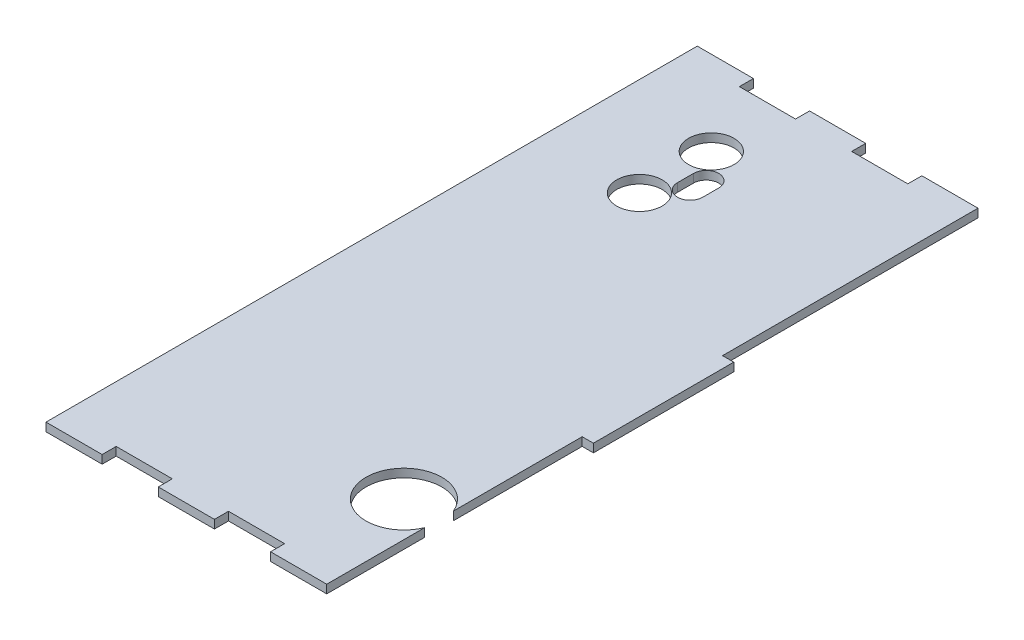
SolidWorks part; units mm, degrees
ref_plane "Front Plane" through (0, 0, 0) normal (0, 0, 1) x (1, 0, 0)
ref_plane "Top Plane" through (0, 0, 0) normal (0, 1, 0) x (1, 0, 0)
ref_plane "Right Plane" through (0, 0, 0) normal (1, 0, 0) x (0, 0, -1)
sketch "Sketch1" plane through (0, 0, 0) normal (0, 1, 0) x (1, 0, 0)
  line L0 (-50, -111) -> (-50, -116)
  line L1 (30, 111) -> (10, 111)
  line L2 (50, 111) -> (50, 25)
  line L3 (30, -111) -> (10, -111)
  line L4 (-50, 111) -> (-50, -111)
  line L5 (50, 111) -> (-50, -111) construction
  line L6 (50, -111) -> (-50, 111) construction
  line L7 (-50, -116) -> (-30, -116)
  line L8 (-30, -116) -> (-30, -111)
  line L9 (-10, -111) -> (-10, -116)
  line L10 (-10, -116) -> (10, -116)
  line L11 (10, -116) -> (10, -111)
  line L12 (30, -111) -> (30, -116)
  line L13 (30, -116) -> (50, -116)
  line L14 (50, -116) -> (50, -111)
  line L15 (-50, 0) -> (50, 0) construction
  line L16 (0, -116) -> (0, 116) construction
  line L17 (50, 116) -> (50, 111)
  line L18 (30, 116) -> (50, 116)
  line L19 (30, 111) -> (30, 116)
  line L20 (10, 116) -> (10, 111)
  line L21 (-10, 116) -> (10, 116)
  line L22 (-10, 111) -> (-10, 116)
  line L23 (-30, 116) -> (-30, 111)
  line L24 (-50, 116) -> (-30, 116)
  line L25 (-50, 111) -> (-50, 116)
  line L26 (-10, 111) -> (-30, 111)
  line L27 (-10, -111) -> (-30, -111)
  line L28 (50, -25) -> (50, -70.901)
  line L29 (50, -25) -> (54, -25)
  line L31 (50, 25) -> (54, 25)
  line L32 (54, -25) -> (54, 25)
  line L35 (-15, 60.4) -> (-15, 86) construction
  line L36 (50, -81.099) -> (50, -111)
  line L37 (-11.4, 70.35) -> (-11.4, 76.05)
  line L38 (-2.4, 70.35) -> (-2.4, 76.05)
  circle A4 centre (-15, 60.4) radius 8.1
  circle A5 centre (-15, 86) radius 8.1
  arc A6 (-11.4, 70.35) -> (-2.4, 70.35) centre (-6.9, 70.35) ccw
  arc A7 (-2.4, 76.05) -> (-11.4, 76.05) centre (-6.9, 76.05) ccw
  arc A8 (50, -70.901) -> (50, -81.099) centre (37.5, -76) ccw
  point P0 (0, 0)
  dimension "D8" = 16.2
  dimension "D9" = 16.2
  dimension "D14" = 9
  dimension "D15" = 9
  dimension "D21" = 27
  dimension "D1" = 100
  dimension "D2" = 222
  dimension "D3" = 5
  dimension "D4" = 20
  dimension "D6" = 50
  dimension "D7" = 4
  dimension "D10" = 25.6
  dimension "D11" = 8.1
  dimension "D12" = 8.1
  dimension "D13" = 5.7
  dimension "D16" = 25
  dimension "D17" = 9.95
  dimension "D18" = 65
  dimension "D19" = 5.7
  dimension "D20" = 5.7
  dimension "D22" = 12.5
  dimension "D23" = 35
  dimension "D24" = 86
  dimension "D5" = 3
extrude "Boss-Extrude1" add sketch "Sketch1" along normal blind 3
